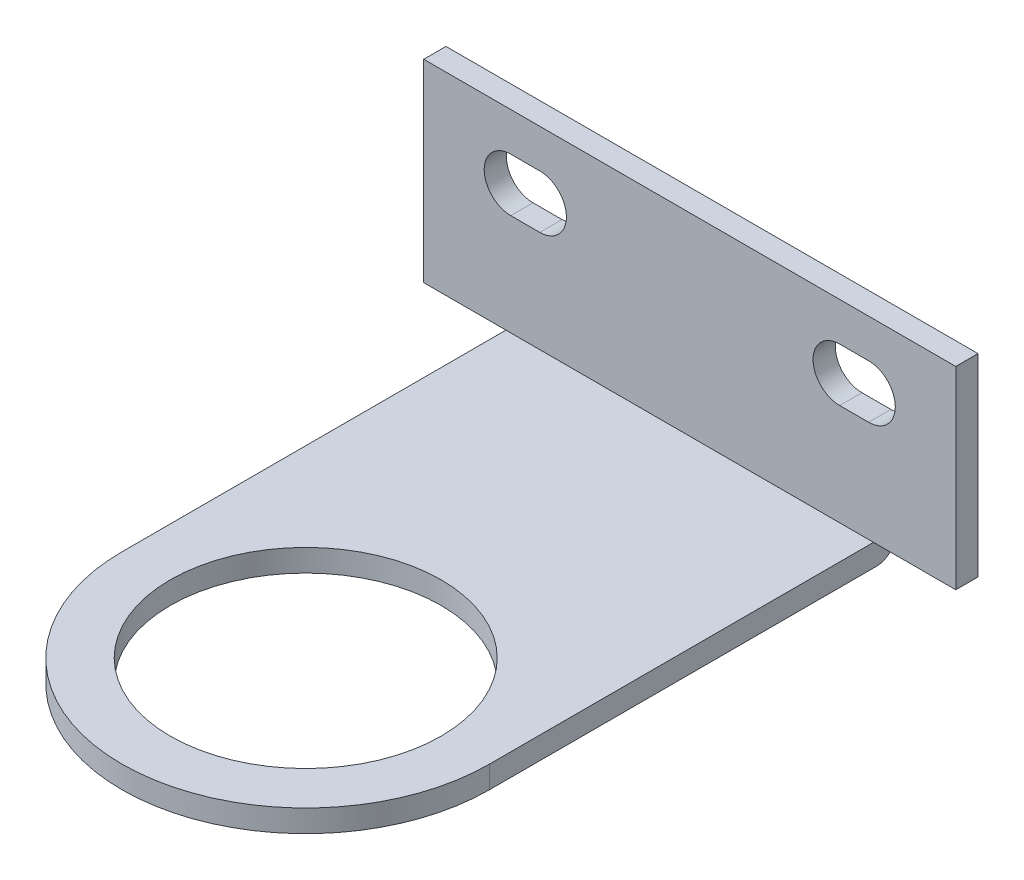
SolidWorks part; units mm, degrees
ref_plane "前视基准面" through (0, 0, 0) normal (0, 0, 1) x (1, 0, 0)
ref_plane "上视基准面" through (0, 0, 0) normal (0, 1, 0) x (1, 0, 0)
ref_plane "右视基准面" through (0, 0, 0) normal (1, 0, 0) x (0, 0, -1)
sketch "草图1" plane through (0, 0, 0) normal (0, 1, 0) x (1, 0, 0)
  line L0 (-19, 0) -> (-19, 42)
  line L1 (19, 0) -> (19, 42)
  line L2 (-19, 42) -> (19, 42)
  circle A0 centre (0, 0) radius 14
  arc A1 (-19, 0) -> (19, 0) centre (0, 0) ccw
  dimension "D1" = 28
  dimension "D2" = 38
extrude "拉伸1" add sketch "草图1" along normal blind 2.3
sketch "草图2" plane through (0, 2.3, 0) normal (0, 1, 0) x (1, 0, 0)
  line L0 (0, 42) -> (27.5, 42)
  line L1 (0, 14) -> (0, 16.0928) construction
  line L2 (0, 14) -> (0, 44.3) construction
  line L3 (0, 42) -> (-27.5, 42)
  line L4 (-27.5, 42) -> (-27.5, 39.7)
  line L6 (27.5, 42) -> (27.5, 39.7)
  line L7 (-27.5, 39.7) -> (27.5, 39.7)
  circle A0 centre (0, 0) radius 14 construction
  dimension "D1" = 27.5
extrude "拉伸2" add sketch "草图2" along normal blind 20
fillet "圆角1" radius 2 1 edges at (0, 0, -42)
sketch "草图3" plane through (0, 0, -42) normal (0, 0, -1) x (-1, 0, 0)
  line L0 (-27.5, 15.55) -> (27.5, 15.55) construction
  line L1 (-27.5, 22.3) -> (-27.5, 2.3) construction
  line L2 (27.5, 22.3) -> (27.5, 2.3) construction
  line L3 (-18.5, 15.55) -> (-15.5, 15.55) construction
  line L4 (-18.5, 18.3) -> (-15.5, 18.3)
  line L5 (-18.5, 12.8) -> (-15.5, 12.8)
  line L6 (15.5, 15.55) -> (18.5, 15.55) construction
  line L7 (15.5, 18.3) -> (18.5, 18.3)
  line L8 (15.5, 12.8) -> (18.5, 12.8)
  line L9 (-27.5, 22.3) -> (27.5, 22.3) construction
  line L10 (0, 2) -> (0, 3.2948) construction
  line L11 (-19, 2) -> (19, 2) construction
  line L12 (0, 24.9669) -> (0, 2) construction
  arc A0 (-18.5, 18.3) -> (-18.5, 12.8) centre (-18.5, 15.55) ccw
  arc A1 (-15.5, 12.8) -> (-15.5, 18.3) centre (-15.5, 15.55) ccw
  arc A2 (15.5, 18.3) -> (15.5, 12.8) centre (15.5, 15.55) ccw
  arc A3 (18.5, 12.8) -> (18.5, 18.3) centre (18.5, 15.55) ccw
  point P8 (-17, 15.55)
  point P15 (17, 15.55)
  dimension "D6" = 31
  dimension "D1" = 5.5
  dimension "D2" = 3
  dimension "D3" = 5.5
  dimension "D4" = 3
  dimension "D5" = 4
  dimension "D7" = 15.5
extrude "拉伸3" cut sketch "草图3" against normal through all
